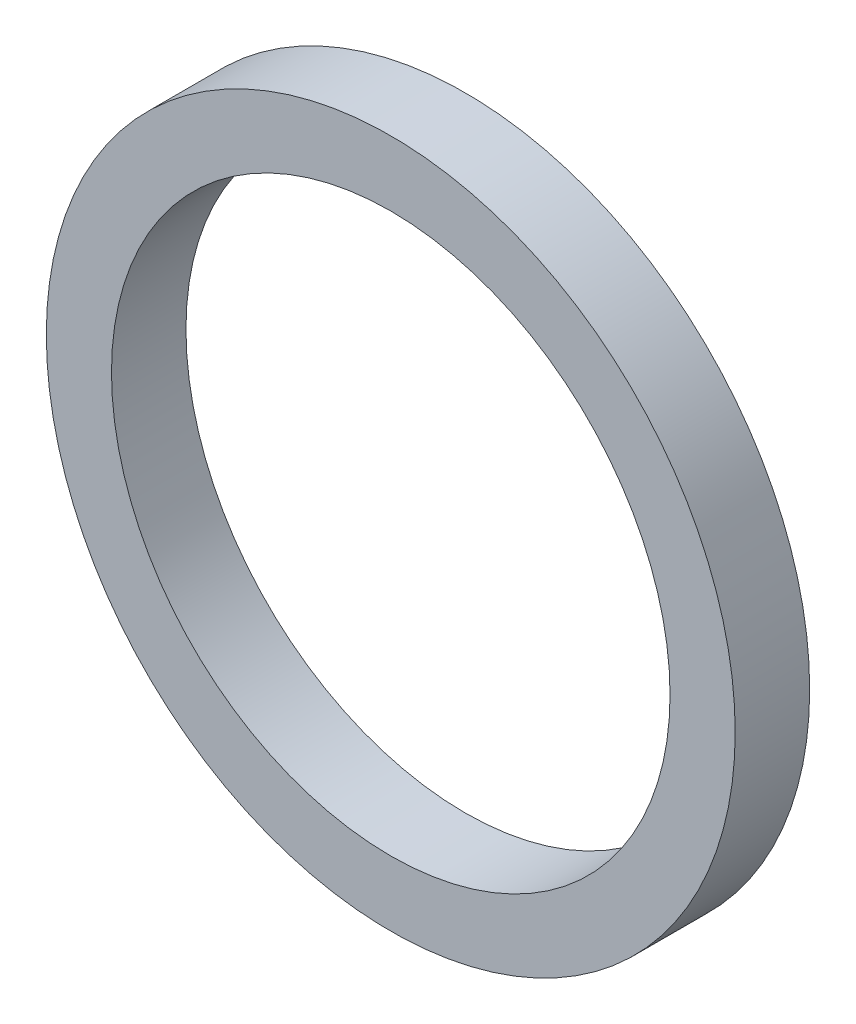
SolidWorks part; units mm, degrees
ref_plane "前视基准面" through (0, 0, 0) normal (0, 0, 1) x (1, 0, 0)
ref_plane "上视基准面" through (0, 0, 0) normal (0, 1, 0) x (1, 0, 0)
ref_plane "右视基准面" through (0, 0, 0) normal (1, 0, 0) x (0, 0, -1)
other "Configuration Table"
sketch "草图1" plane through (0, 0, 0) normal (0, 0, 1) x (1, 0, 0)
  circle A0 centre (0, 0) radius 18.5
  circle A1 centre (0, 0) radius 15
  dimension "D1" = 37
  dimension "D2" = 30
extrude "凸台-拉伸1" add sketch "草图1" along normal blind 4
